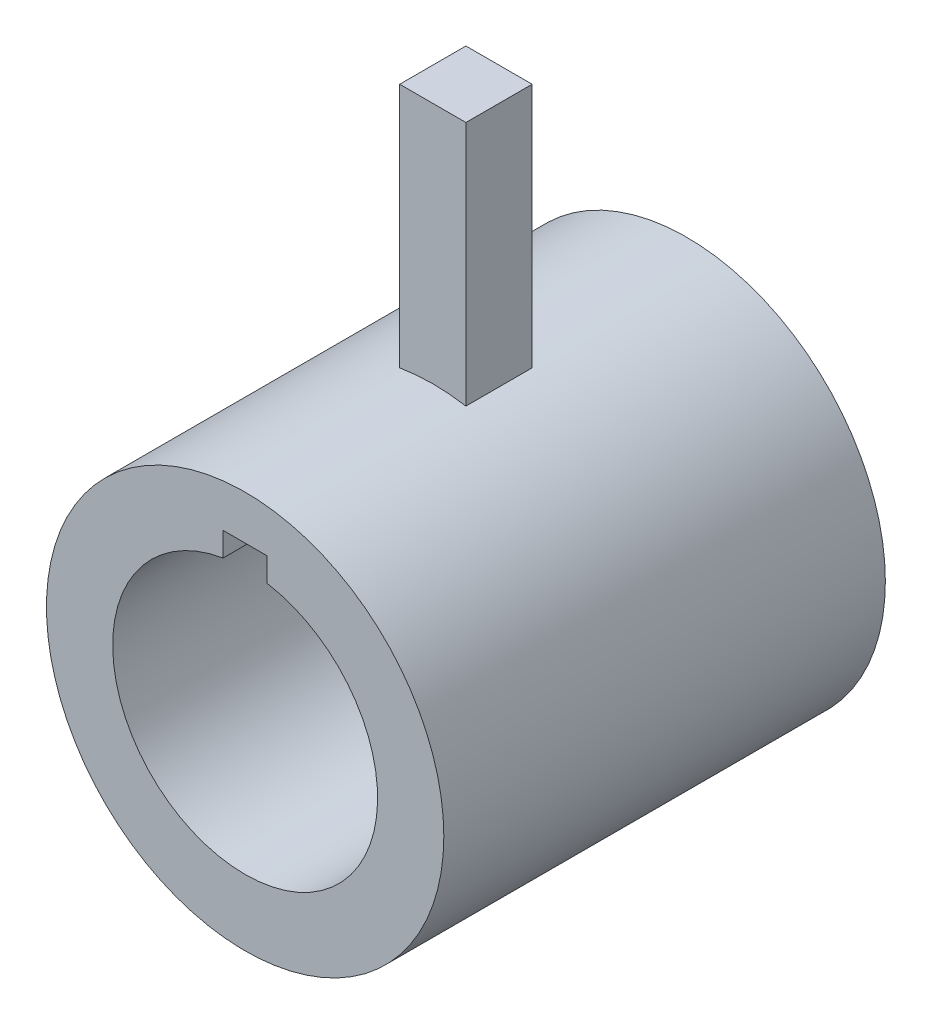
SolidWorks part; units mm, degrees
ref_plane "Front Plane" through (0, 0, 0) normal (0, 0, 1) x (1, 0, 0)
ref_plane "Top Plane" through (0, 0, 0) normal (0, 1, 0) x (1, 0, 0)
ref_plane "Right Plane" through (0, 0, 0) normal (1, 0, 0) x (0, 0, -1)
sketch "Sketch1" plane through (0, 0, 0) normal (0, 0, 1) x (1, 0, 0)
  line L6 (0.5, 2.958) -> (0.5, 3.5)
  line L7 (0, 3) -> (0, 4.5) construction
  line L8 (0.5, 3.5) -> (-0.5, 3.5)
  line L9 (-0.5, 2.958) -> (-0.5, 3.5)
  line L10 (0, 3) -> (-0.5, 3.5) construction
  line L11 (0.5, 3.5) -> (0, 3) construction
  circle A0 centre (0, 0) radius 4.5
  arc A1 (-0.5, 2.958) -> (0.5, 2.958) centre (0, 0) ccw
  point P3 (0, 3)
  dimension "D1" = 6
  dimension "D2" = 9
  dimension "D3" = 0.542
  dimension "D4" = 1
  dimension "D5" = 0.542
extrude "Boss-Extrude1" add sketch "Sketch1" along normal blind 10 contours A0
sketch "Sketch3" plane through (0, 0, 0) normal (0, 1, 0) x (1, 0, 0)
  line L0 (0, 0) -> (0, -10) construction
  line L1 (-4.5, -10) -> (4.5, -10) construction
  line L3 (-0.75, -5.75) -> (0.75, -5.75)
  line L4 (-0.75, -5.75) -> (-0.75, -4.25)
  line L5 (-0.75, -4.25) -> (0.75, -4.25)
  line L6 (0.75, -5.75) -> (0.75, -4.25)
  line L7 (-0.75, -5.75) -> (0.75, -4.25) construction
  line L8 (-0.75, -4.25) -> (0.75, -5.75) construction
  point P5 (0, -5)
  dimension "D1" = 1.5
  dimension "D2" = 1.5
extrude "Boss-Extrude3" add sketch "Sketch3" along normal blind 6 from offset 4
